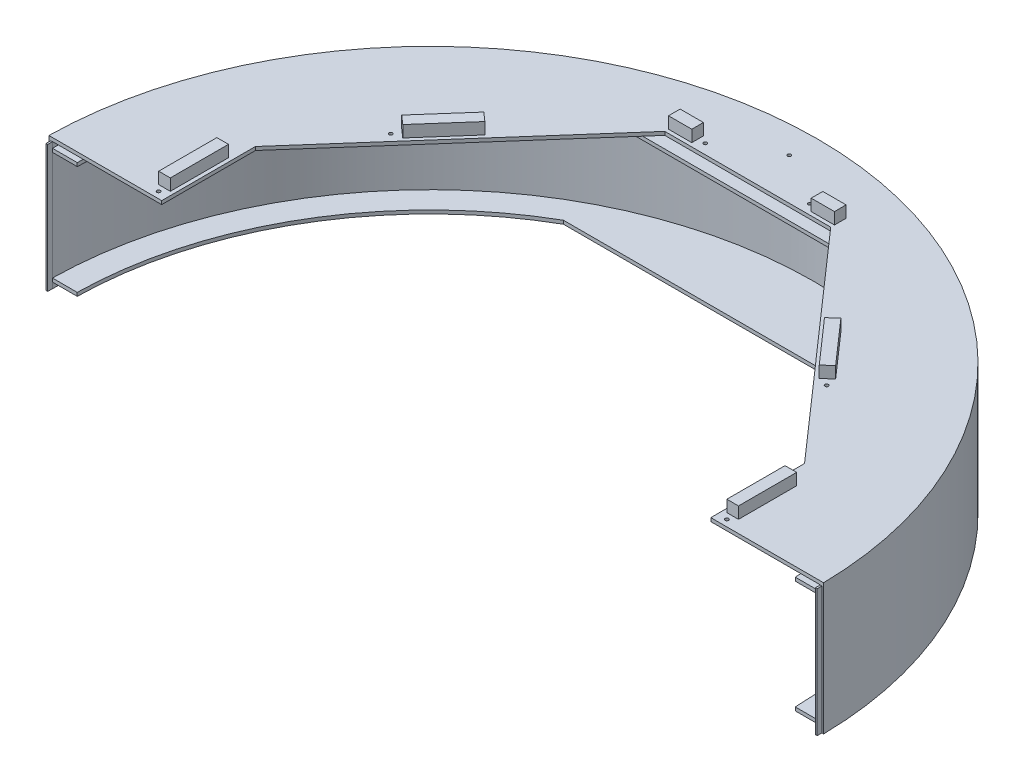
SolidWorks part; units mm, degrees
ref_plane "Front Plane" through (0, 0, 0) normal (0, 0, 1) x (1, 0, 0)
ref_plane "Top Plane" through (0, 0, 0) normal (0, 1, 0) x (1, 0, 0)
ref_plane "Right Plane" through (0, 0, 0) normal (1, 0, 0) x (0, 0, -1)
sketch "Sketch3" plane through (0, 0, 0) normal (0, 1, 0) x (1, 0, 0)
  line L0 (-251.0083, -74.5986) -> (228.9917, -74.5986) construction
  line L1 (228.9917, -74.5986) -> (-11.0083, 165.4014) construction
  line L2 (-11.0083, 165.4014) -> (-251.0083, -74.5986) construction
  line L3 (-11.0083, 165.4014) -> (-11.0083, -74.5986) construction
  line L4 (-230.0083, 0.4014) -> (-230.0083, -149.5986) construction
  line L5 (-230.0083, -149.5986) -> (-272.0083, -149.5986) construction
  line L6 (-272.0083, -149.5986) -> (-272.0083, -169.5986) construction
  line L7 (-161.0083, -209.5986) -> (138.9917, -209.5986) construction
  line L8 (-230.0083, 0.4014) -> (-272.0083, 0.4014) construction
  line L9 (-272.0083, 0.4014) -> (-272.0083, 110.4014) construction
  line L10 (-272.0083, 110.4014) -> (-121.0083, 282.0601) construction
  line L11 (-161.0083, -209.5986) -> (-272.0083, -169.5986) construction
  line L12 (249.9917, 110.4014) -> (98.9917, 282.0601) construction
  line L13 (138.9917, -209.5986) -> (249.9917, -169.5986) construction
  line L14 (249.9917, -149.5986) -> (249.9917, -169.5986) construction
  line L15 (207.9917, -149.5986) -> (249.9917, -149.5986) construction
  line L16 (207.9917, 0.4014) -> (207.9917, -149.5986) construction
  line L17 (207.9917, 0.4014) -> (249.9917, 0.4014) construction
  line L18 (249.9917, 0.4014) -> (249.9917, 110.4014) construction
  arc A0 (98.9917, 282.0601) -> (-121.0083, 282.0601) centre (-11.0083, 187.4993) ccw construction
  circle A1 centre (-11.0083, 15.1744) radius 330
  circle A2 centre (-11.0083, 15.1744) radius 333
  point P22 (-11.0083, 282.0601)
  dimension "D1" = 480
  dimension "D2" = 21
  dimension "D3" = 75
  dimension "D4" = 75
  dimension "D5" = 42
  dimension "D6" = 20
  dimension "D7" = 110
  dimension "D8" = 110
  dimension "D9" = 240
  dimension "D10" = 20
  dimension "D11" = 21
  dimension "D12" = 21
  dimension "D13" = 150
  dimension "D14" = 42
  dimension "D15" = 300
  dimension "D16" = 3
extrude "Boss-Extrude2" add sketch "Sketch3" along normal blind 3 and the other way blind 109.6
ref_plane "Plane2" through (0, -104.6, 0) normal (0, -1, 0) x (-1, 0, 0)
sketch "Sketch5" plane through (0, -104.6, 0) normal (0, -1, 0) x (1, 0, 0)
  line L0 (-166.0669, -282.0601) -> (144.0503, -282.0601) construction
  line L1 (-164.3328, -283.0601) -> (142.3162, -283.0601)
  circle A0 centre (-11.0083, -15.1744) radius 330
  circle A1 centre (-11.0083, -15.1744) radius 308.6602 construction
  arc A2 (-164.3328, -283.0601) -> (142.3162, -283.0601) centre (-11.0083, -15.1744) cw
  dimension "D1" = 1
extrude "Boss-Extrude4" add sketch "Sketch5" against normal blind 3
sketch "Sketch6" plane through (0, 0, 0) normal (0, 1, 0) x (1, 0, 0)
  line L0 (-272.0083, 0.4014) -> (-272.0083, 110.4014) construction
  line L1 (249.9917, 0.4014) -> (249.9917, 110.4014) construction
  line L2 (249.9917, 110.4014) -> (98.9917, 282.0601) construction
  line L3 (-272.0083, 110.4014) -> (-121.0083, 282.0601) construction
  line L4 (-82.3339, 288.1744) -> (60.3173, 288.1744)
  line L5 (-100.8342, 348.1744) -> (51.1218, 348.1744) construction
  line L6 (-247.0083, 20.4014) -> (-247.0083, 100.9705)
  line L7 (-230.0083, 0.4014) -> (-230.0083, -149.5986) construction
  line L8 (-247.0083, 20.4014) -> (-210.0083, 20.4014)
  line L9 (224.9917, 20.4014) -> (224.9917, 100.9705)
  line L10 (207.9917, 0.4014) -> (249.9917, 0.4014) construction
  line L11 (224.9917, 20.4014) -> (187.9917, 20.4014)
  line L12 (-247.0083, 100.9705) -> (-82.3339, 288.1744)
  line L13 (224.9917, 100.9705) -> (60.3173, 288.1744)
  line L14 (-210.0083, 20.4014) -> (-210.0083, -191.941) construction
  line L15 (187.9917, 20.4014) -> (187.9917, -191.941) construction
  line L16 (138.9917, -209.5986) -> (249.9917, -169.5986) construction
  line L17 (-161.0083, -209.5986) -> (-272.0083, -169.5986) construction
  line L18 (-210.0083, -189.5986) -> (187.9917, -189.5986)
  line L19 (-161.0083, -209.5986) -> (138.9917, -209.5986) construction
  line L20 (-210.0083, 20.4014) -> (-210.0083, -189.5986)
  line L21 (187.9917, -189.5986) -> (187.9917, 20.4014)
  line L22 (-230.0083, 0.4014) -> (-272.0083, 0.4014) construction
  circle A0 centre (-11.0083, 15.1744) radius 333
  circle A1 centre (-11.0083, 15.1744) radius 273 construction
  dimension "D1" = 60
  dimension "D2" = 25
  dimension "D3" = 25
  dimension "D4" = 25
  dimension "D5" = 25
  dimension "D6" = 60
  dimension "D7" = 20
  dimension "D8" = 20
  dimension "D9" = 20
  dimension "D10" = 20
extrude "Boss-Extrude6" add sketch "Sketch6" along normal blind 3 contours A0 L21 L18 L20 L8 L6 L12 L4 L13 L9 L11
ref_plane "Plane4" through (0, -5, 0) normal (0, 1, 0) x (1, 0, 0)
sketch "Sketch17" plane through (0, -5, 0) normal (0, 1, 0) x (1, 0, 0)
  line L2 (142.3162, 283.0601) -> (-164.3328, 283.0601)
  line L3 (142.3162, 283.0601) -> (-164.3328, 283.0601)
  arc A2 (-164.3328, 283.0601) -> (142.3162, 283.0601) centre (-11.0083, 15.1744) ccw
  arc A3 (-164.3328, 283.0601) -> (142.3162, 283.0601) centre (-11.0083, 15.1744) ccw
  circle A5 centre (-11.0083, 15.1744) radius 330
  circle A6 centre (-11.0083, 15.1744) radius 330
  dimension "D1" = 0
  dimension "D2" = 0
extrude "Boss-Extrude9" add sketch "Sketch17" against normal blind 3
sketch "Sketch18" plane through (0, 3, 0) normal (0, 1, 0) x (1, 0, 0)
  line L1 (-363.4395, 20.4014) -> (358.1118, 20.4014)
  line L2 (-363.4395, 20.4014) -> (-363.4395, -328.4214)
  line L3 (-363.4395, -328.4214) -> (358.1118, -328.4214)
  line L4 (358.1118, 20.4014) -> (358.1118, -328.4214)
extrude "Cut-Extrude1" cut sketch "Sketch18" against normal through all both and the other way through all
sketch "Sketch19" plane through (0, 3, 0) normal (0, 1, 0) x (1, 0, 0)
  line L0 (-190.0053, 170.6172) -> (-156.9813, 208.1593)
  line L1 (-156.9813, 208.1593) -> (-164.4897, 214.7641)
  line L2 (-164.4897, 214.7641) -> (-197.5137, 177.222)
  line L3 (-197.5137, 177.222) -> (-190.0053, 170.6172)
  line L4 (167.9887, 170.6172) -> (134.9647, 208.1593)
  line L5 (224.9917, 100.9705) -> (60.3173, 288.1744) construction
  line L6 (134.9647, 208.1593) -> (142.4731, 214.7641)
  line L7 (142.4731, 214.7641) -> (175.4971, 177.222)
  line L8 (175.4971, 177.222) -> (167.9887, 170.6172)
  line L9 (-247.0083, 100.9705) -> (-82.3339, 288.1744) construction
  line L11 (-247.0083, 20.4014) -> (-247.0083, 100.9705) construction
  line L12 (-250.2083, 81.01) -> (-260.2083, 81.01)
  line L13 (-250.2083, 81.01) -> (-250.2083, 31.01)
  line L14 (-250.2083, 31.01) -> (-260.2083, 31.01)
  line L15 (-260.2083, 81.01) -> (-260.2083, 31.01)
  line L16 (228.1917, 81.01) -> (238.1917, 81.01)
  line L17 (228.1917, 81.01) -> (228.1917, 31.01)
  line L18 (228.1917, 31.01) -> (238.1917, 31.01)
  line L19 (238.1917, 81.01) -> (238.1917, 31.01)
  line L20 (224.9917, 20.4014) -> (224.9917, 100.9705) construction
  line L26 (-82.3339, 291.3744) -> (-62.3339, 291.3744)
  line L27 (-82.3339, 291.3744) -> (-82.3339, 301.3744)
  line L28 (-82.3339, 301.3744) -> (-62.3339, 301.3744)
  line L29 (-62.3339, 291.3744) -> (-62.3339, 301.3744)
  line L30 (60.3173, 291.3744) -> (40.3173, 291.3744)
  line L31 (60.3173, 291.3744) -> (60.3173, 301.3744)
  line L32 (60.3173, 301.3744) -> (40.3173, 301.3744)
  line L33 (40.3173, 291.3744) -> (40.3173, 301.3744)
  dimension "D1" = 50
  dimension "D2" = 10
  dimension "D3" = 3.2
  dimension "D4" = 3.2
  dimension "D5" = 90
  dimension "D6" = 90
  dimension "D7" = 3.2
  dimension "D8" = 3.2
  dimension "D9" = 20
  dimension "D10" = 10
  dimension "D11" = 50
  dimension "D12" = 20
extrude "Boss-Extrude10" add sketch "Sketch19" along normal blind 10
ref_plane "Plane5" through (-343.9673, 3, -20.4014) normal (-0.0157, 0, 0.9999) x (0.9999, 0, 0.0157)
sketch "Sketch23" plane through (0, 0, -20.4014) normal (0, 0, 1) x (1, 0, 0)
  line L0 (318.9503, -0.2) -> (318.9503, -109.6)
  line L2 (318.9503, -109.6) -> (320.4505, -109.6)
  line L3 (321.9507, -109.6) -> (318.9503, -109.6) construction
  line L4 (320.4505, -109.6) -> (320.4505, -0.2)
  line L5 (318.9503, -0.2) -> (320.4505, -0.2)
  line L6 (-340.9669, -109.6) -> (-342.4671, -109.6)
  line L7 (-340.9669, -109.6) -> (-343.9673, -109.6) construction
  line L8 (-340.9669, -0.2) -> (-340.9669, -109.6)
  line L9 (-342.4671, -109.6) -> (-342.4671, -0.2)
  line L10 (-342.4671, -0.2) -> (-340.9669, -0.2)
  dimension "D1" = 0.2
  dimension "D2" = 0.2
extrude "Boss-Extrude11" add sketch "Sketch23" along normal blind 4
sketch "Sketch25" plane through (0, 3, 0) normal (0, 1, 0) x (1, 0, 0)
  circle A0 centre (-56.0083, 296.6679) radius 1.5
  circle A1 centre (33.9917, 296.6679) radius 1.5
  circle A2 centre (-11.0083, 323.8346) radius 1.5
  circle A3 centre (-11.0083, 15.1744) radius 308.6602 construction
  circle A4 centre (-198.3764, 168.6711) radius 1.5
  circle A5 centre (176.3598, 168.6711) radius 1.5
  circle A6 centre (-255.2083, 25.9785) radius 1.5
  circle A7 centre (233.1917, 25.9785) radius 1.5
extrude "Cut-Extrude2" cut sketch "Sketch25" against normal up to surface (11 mm away)
equation "\"camera-height\"= 100mm"
equation "\"case-thickness\"= 3mm"
equation "\"D16@Sketch3\"=\"case-thickness\""
equation "\"D1@Boss-Extrude2\"=\"case-thickness\""
